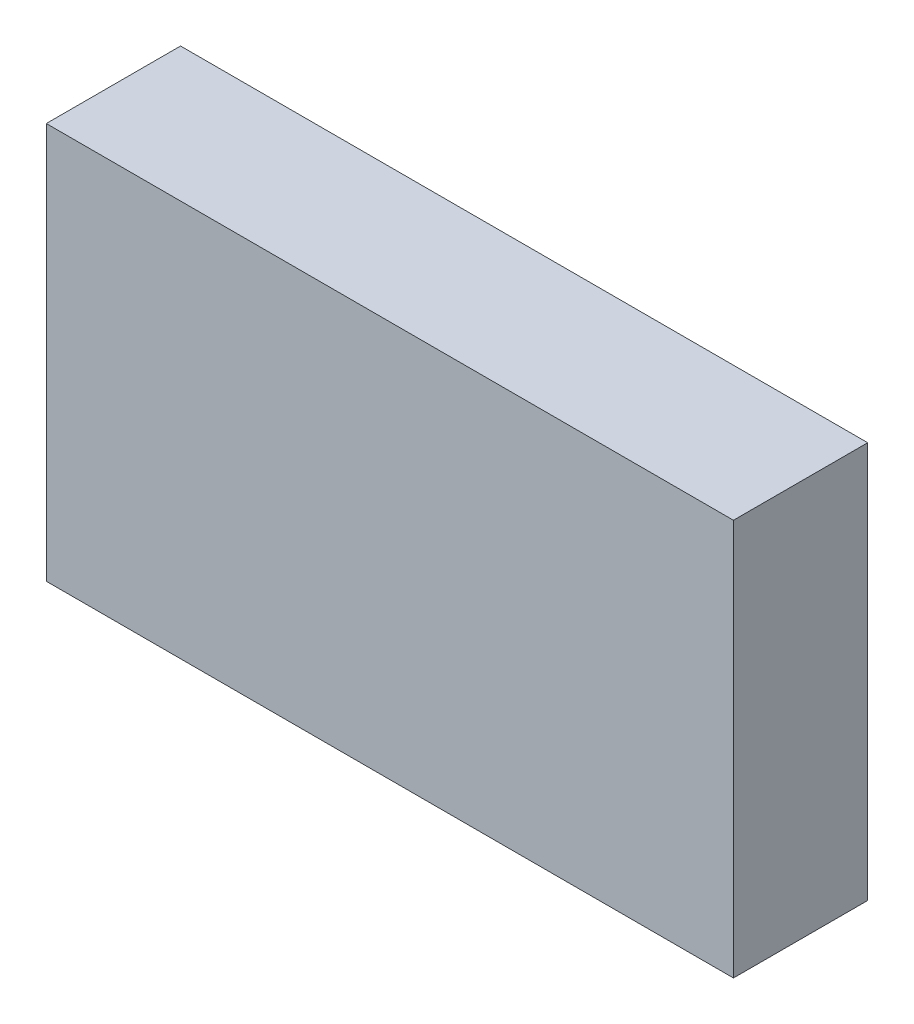
SolidWorks part; units mm, degrees
material "Low Carbon Steel"
ref_plane "Front Plane" through (0, 0, 0) normal (0, 0, 1) x (1, 0, 0)
ref_plane "Top Plane" through (0, 0, 0) normal (0, 1, 0) x (1, 0, 0)
ref_plane "Right Plane" through (0, 0, 0) normal (1, 0, 0) x (0, 0, -1)
sketch "Sketch3" plane through (0, 0, 0) normal (0, 0, 1) x (1, 0, 0)
  line L1 (-65, 0) -> (65, 0)
  line L2 (-65, 0) -> (-65, -75)
  line L3 (-65, -75) -> (65, -75)
  line L4 (65, 0) -> (65, -75)
  dimension "D1" = 130
  dimension "D2" = 75
extrude "Boss-Extrude1" add sketch "Sketch3" along normal blind 25.4
other "Freeze***"
